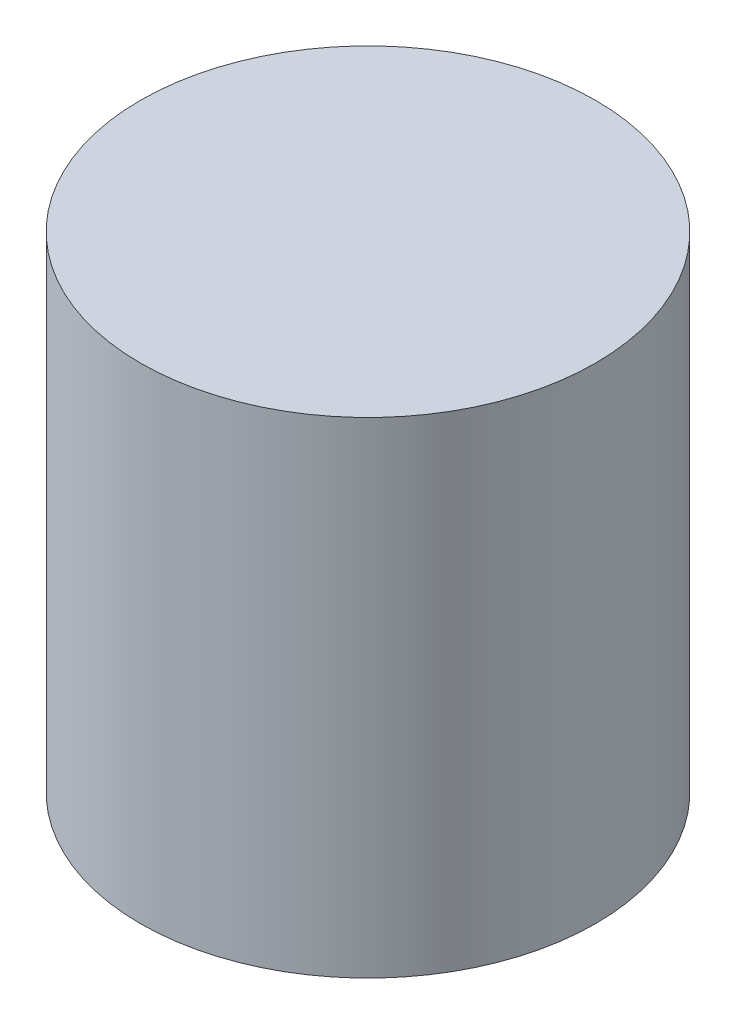
SolidWorks part; units mm, degrees
ref_plane "Front Plane" through (0, 0, 0) normal (0, 0, 1) x (1, 0, 0)
ref_plane "Top Plane" through (0, 0, 0) normal (0, 1, 0) x (1, 0, 0)
ref_plane "Right Plane" through (0, 0, 0) normal (1, 0, 0) x (0, 0, -1)
sketch "Sketch1" plane through (0, 0, 0) normal (0, 1, 0) x (1, 0, 0)
  circle A0 centre (0, 0) radius 7.5
  dimension "D1" = 15
extrude "Boss-Extrude1" add sketch "Sketch1" along normal blind 16
